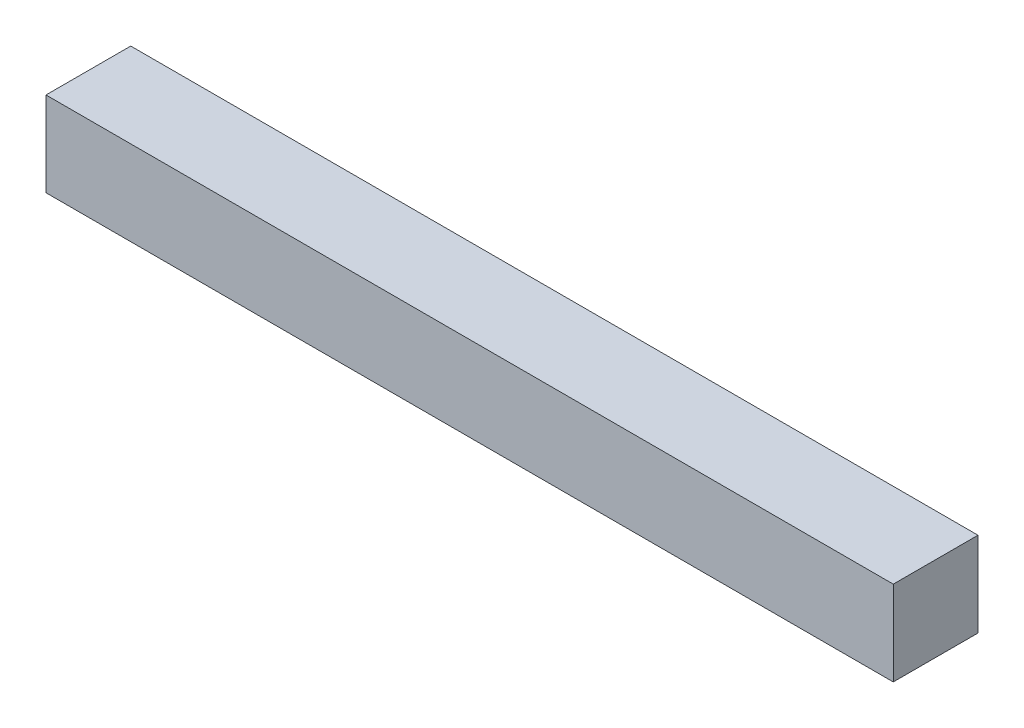
SolidWorks part; units mm, degrees
ref_plane "Plan de face" through (0, 0, 0) normal (0, 0, 1) x (1, 0, 0)
ref_plane "Plan de dessus" through (0, 0, 0) normal (0, 1, 0) x (1, 0, 0)
ref_plane "Plan de droite" through (0, 0, 0) normal (1, 0, 0) x (0, 0, -1)
sketch "Esquisse1" plane through (0, 0, 0) normal (1, 0, 0) x (0, 0, -1)
  line L1 (-5, -5) -> (5, -5)
  line L2 (-5, -5) -> (-5, 5)
  line L3 (-5, 5) -> (5, 5)
  line L4 (5, -5) -> (5, 5)
  line L5 (-5, -5) -> (5, 5) construction
  line L6 (-5, 5) -> (5, -5) construction
  point P0 (0, 0)
  dimension "D1" = 10
  dimension "D2" = 10
extrude "Boss.-Extru.1" add sketch "Esquisse1" along normal blind 100
